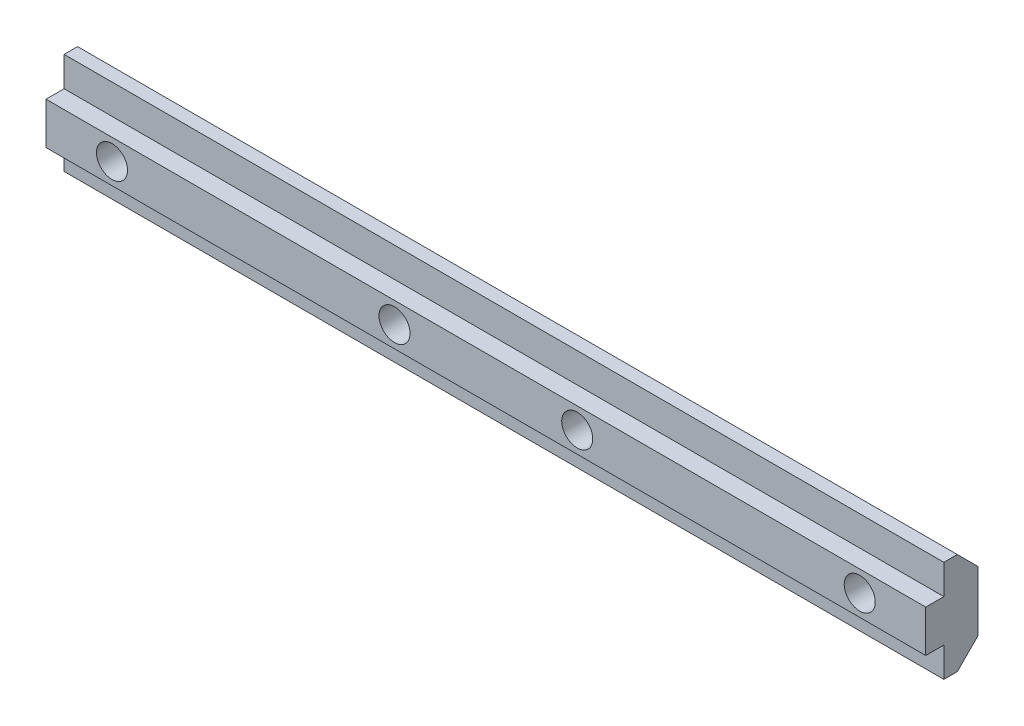
SolidWorks part; units mm, degrees
ref_plane "前视基准面" through (0, 0, 0) normal (0, 0, 1) x (1, 0, 0)
ref_plane "上视基准面" through (0, 0, 0) normal (0, 1, 0) x (1, 0, 0)
ref_plane "右视基准面" through (0, 0, 0) normal (1, 0, 0) x (0, 0, -1)
sketch "草图1" plane through (0, 0, 0) normal (0, 0, 1) x (1, 0, 0)
  line L1 (-85, -9.8) -> (85, -9.8)
  line L2 (-85, -9.8) -> (-85, 9.8)
  line L3 (-85, 9.8) -> (85, 9.8)
  line L4 (85, -9.8) -> (85, 9.8)
  line L5 (-85, -9.8) -> (85, 9.8) construction
  line L6 (-85, 9.8) -> (85, -9.8) construction
  point P0 (0, 0)
  dimension "D1" = 170
  dimension "D2" = 19.6
extrude "凸台-拉伸1" add sketch "草图1" along normal blind 6.6
sketch "草图2" plane through (0, 0, 6.6) normal (0, 0, 1) x (1, 0, 0)
  line L0 (85, -9.8) -> (85, 9.8) construction
  line L1 (-85, -4.05) -> (85, -4.05)
  line L2 (-85, -4.05) -> (-85, 4.05)
  line L3 (-85, 4.05) -> (85, 4.05)
  line L4 (85, -4.05) -> (85, 4.05)
  line L5 (-85, -4.05) -> (85, 4.05) construction
  line L6 (-85, 4.05) -> (85, -4.05) construction
  point P1 (0, 0)
  dimension "D1" = 8.1
extrude "凸台-拉伸2" add sketch "草图2" along normal blind 3.5
sketch "草图3" plane through (0, 0, 10.1) normal (0, 0, 1) x (1, 0, 0)
  line L0 (0, 0) -> (0, 4.05) construction
  line L1 (85, 4.05) -> (-85, 4.05) construction
  circle A0 centre (-72.2471, 0) radius 3
  circle A1 centre (-17.6534, 0) radius 3
  circle A2 centre (17.6534, 0) radius 3
  circle A3 centre (72.2471, 0) radius 3
  dimension "D1" = 6
  dimension "D2" = 6
extrude "切除-拉伸1" cut sketch "草图3" against normal through all
chamfer "倒角1" distance 4 angle 45 2 edges at (0, -9.8, 0) (0, 9.8, 0)
